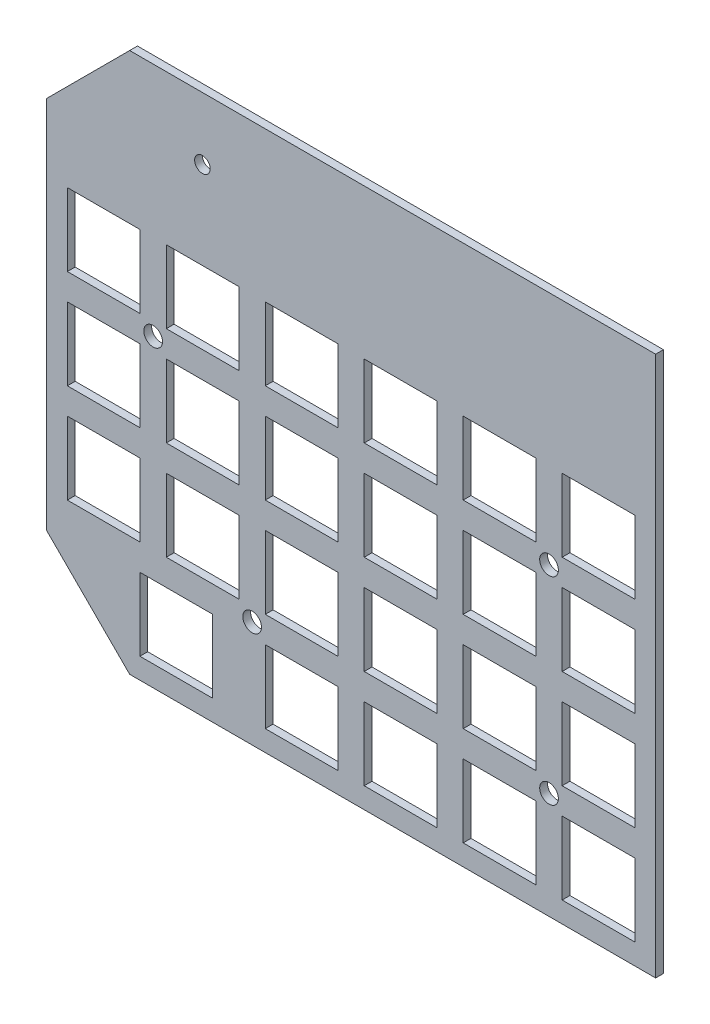
SolidWorks part; units mm, degrees
material "Alliage 1060"
ref_plane "Plan de face" through (0, 0, 0) normal (0, 0, 1) x (1, 0, 0)
ref_plane "Plan de dessus" through (0, 0, 0) normal (0, 1, 0) x (1, 0, 0)
ref_plane "Plan de droite" through (0, 0, 0) normal (1, 0, 0) x (0, 0, -1)
other "Centre de masse"
sketch "Esquisse1" plane through (0, 0, 0) normal (0, 0, 1) x (1, 0, 0)
  line L0 (0, -85) -> (16, -101)
  line L4 (117.25, 3) -> (117.25, -101)
  line L5 (16, 3) -> (0, -13)
  line L7 (117.25, 3) -> (16, 3)
  line L8 (0, -13) -> (0, -85)
  line L9 (16, -101) -> (117.25, -101)
  dimension "D1" = 104
  dimension "D2" = 117.25
  dimension "D3" = 16
  dimension "D4" = 16
  dimension "D5" = 16
  dimension "D6" = 16
extrude "Boss.-Extru.1" add sketch "Esquisse1" along normal blind 1.5
sketch "Esquisse2" plane through (0, 0, 1.5) normal (0, 0, 1) x (1, 0, 0)
  line L0 (0, -13) -> (0, -85) construction
  line L1 (4, -25.85) -> (18, -25.85)
  line L2 (4, -25.85) -> (4, -39.85)
  line L3 (4, -39.85) -> (18, -39.85)
  line L4 (18, -25.85) -> (18, -39.85)
  line L5 (11, -39.85) -> (11, -25.85) construction
  line L6 (4, -32.85) -> (18, -32.85) construction
  line L7 (117.25, 3) -> (16, 3) construction
  line L8 (117.25, -101) -> (117.25, 3) construction
  line L12 (23.05, -25.85) -> (23.05, -39.85)
  line L13 (23.05, -25.85) -> (37.05, -25.85)
  line L14 (37.05, -25.85) -> (37.05, -39.85)
  line L15 (23.05, -39.85) -> (37.05, -39.85)
  line L16 (42.1, -25.85) -> (42.1, -39.85)
  line L17 (42.1, -25.85) -> (56.1, -25.85)
  line L18 (56.1, -25.85) -> (56.1, -39.85)
  line L19 (42.1, -39.85) -> (56.1, -39.85)
  line L20 (61.15, -25.85) -> (61.15, -39.85)
  line L21 (61.15, -25.85) -> (75.15, -25.85)
  line L22 (75.15, -25.85) -> (75.15, -39.85)
  line L23 (61.15, -39.85) -> (75.15, -39.85)
  line L24 (80.2, -25.85) -> (80.2, -39.85)
  line L25 (80.2, -25.85) -> (94.2, -25.85)
  line L26 (94.2, -25.85) -> (94.2, -39.85)
  line L27 (80.2, -39.85) -> (94.2, -39.85)
  line L28 (99.25, -25.85) -> (99.25, -39.85)
  line L29 (99.25, -25.85) -> (113.25, -25.85)
  line L30 (113.25, -25.85) -> (113.25, -39.85)
  line L31 (99.25, -39.85) -> (113.25, -39.85)
  line L32 (23.05, -44.9) -> (23.05, -58.9)
  line L33 (23.05, -44.9) -> (37.05, -44.9)
  line L34 (37.05, -44.9) -> (37.05, -58.9)
  line L35 (23.05, -58.9) -> (37.05, -58.9)
  line L36 (42.1, -44.9) -> (42.1, -58.9)
  line L37 (42.1, -44.9) -> (56.1, -44.9)
  line L38 (56.1, -44.9) -> (56.1, -58.9)
  line L39 (42.1, -58.9) -> (56.1, -58.9)
  line L40 (61.15, -44.9) -> (61.15, -58.9)
  line L41 (61.15, -44.9) -> (75.15, -44.9)
  line L42 (75.15, -44.9) -> (75.15, -58.9)
  line L43 (61.15, -58.9) -> (75.15, -58.9)
  line L44 (80.2, -44.9) -> (80.2, -58.9)
  line L45 (80.2, -44.9) -> (94.2, -44.9)
  line L46 (94.2, -44.9) -> (94.2, -58.9)
  line L47 (80.2, -58.9) -> (94.2, -58.9)
  line L48 (99.25, -44.9) -> (99.25, -58.9)
  line L49 (99.25, -44.9) -> (113.25, -44.9)
  line L50 (113.25, -44.9) -> (113.25, -58.9)
  line L51 (99.25, -58.9) -> (113.25, -58.9)
  line L52 (23.05, -63.95) -> (23.05, -77.95)
  line L53 (23.05, -63.95) -> (37.05, -63.95)
  line L54 (37.05, -63.95) -> (37.05, -77.95)
  line L55 (23.05, -77.95) -> (37.05, -77.95)
  line L56 (42.1, -63.95) -> (42.1, -77.95)
  line L57 (42.1, -63.95) -> (56.1, -63.95)
  line L58 (56.1, -63.95) -> (56.1, -77.95)
  line L59 (42.1, -77.95) -> (56.1, -77.95)
  line L60 (61.15, -63.95) -> (61.15, -77.95)
  line L61 (61.15, -63.95) -> (75.15, -63.95)
  line L62 (75.15, -63.95) -> (75.15, -77.95)
  line L63 (61.15, -77.95) -> (75.15, -77.95)
  line L64 (80.2, -63.95) -> (80.2, -77.95)
  line L65 (80.2, -63.95) -> (94.2, -63.95)
  line L66 (94.2, -63.95) -> (94.2, -77.95)
  line L67 (80.2, -77.95) -> (94.2, -77.95)
  line L68 (99.25, -63.95) -> (99.25, -77.95)
  line L69 (99.25, -63.95) -> (113.25, -63.95)
  line L70 (113.25, -63.95) -> (113.25, -77.95)
  line L71 (99.25, -77.95) -> (113.25, -77.95)
  line L72 (4, -44.9) -> (4, -58.9)
  line L73 (4, -44.9) -> (18, -44.9)
  line L74 (18, -44.9) -> (18, -58.9)
  line L75 (4, -58.9) -> (18, -58.9)
  line L76 (4, -63.95) -> (4, -77.95)
  line L77 (4, -63.95) -> (18, -63.95)
  line L78 (18, -63.95) -> (18, -77.95)
  line L79 (4, -77.95) -> (18, -77.95)
  line L112 (42.1, -83) -> (42.1, -97)
  line L113 (42.1, -83) -> (56.1, -83)
  line L114 (56.1, -83) -> (56.1, -97)
  line L115 (42.1, -97) -> (56.1, -97)
  line L116 (61.15, -83) -> (61.15, -97)
  line L117 (61.15, -83) -> (75.15, -83)
  line L118 (75.15, -83) -> (75.15, -97)
  line L119 (61.15, -97) -> (75.15, -97)
  line L120 (80.2, -83) -> (80.2, -97)
  line L121 (80.2, -83) -> (94.2, -83)
  line L122 (94.2, -83) -> (94.2, -97)
  line L123 (80.2, -97) -> (94.2, -97)
  line L124 (99.25, -83) -> (99.25, -97)
  line L125 (99.25, -83) -> (113.25, -83)
  line L126 (113.25, -83) -> (113.25, -97)
  line L127 (99.25, -97) -> (113.25, -97)
  line L128 (4, -83) -> (4, -97) [skipped]
  line L129 (4, -83) -> (18, -83) [skipped]
  line L130 (18, -83) -> (18, -97) [skipped]
  line L131 (4, -97) -> (18, -97) [skipped]
  line L132 (23.05, -83) -> (23.05, -97) [skipped]
  line L133 (23.05, -83) -> (37.05, -83) [skipped]
  line L134 (37.05, -83) -> (37.05, -97) [skipped]
  line L135 (23.05, -97) -> (37.05, -97) [skipped]
  line L137 (17.97, -83) -> (31.97, -83)
  line L138 (17.97, -83) -> (17.97, -97)
  line L139 (17.97, -97) -> (31.97, -97)
  line L140 (31.97, -83) -> (31.97, -97)
  line L141 (24.97, -97) -> (24.97, -83) construction
  line L142 (17.97, -90) -> (31.97, -90) construction
  line L143 (16, -101) -> (117.25, -101) construction
  circle A8 centre (30, -9) radius 1.5
  point P0 (11, -32.85)
  point P19 (24.97, -90)
  dimension "D5" = 4
  dimension "D13" = 5.05
  dimension "D7" = 12
  dimension "D6" = 30
  dimension "D1" = 14
  dimension "D2" = 14
  dimension "D3" = 4
  dimension "D4" = 6
  dimension "D9" = 14
  dimension "D10" = 14
  dimension "D11" = 10.13
  dimension "D12" = 5.05
  dimension "D8" = 4
extrude "Enlèv. mat.-Extru.1" cut sketch "Esquisse2" against normal blind 1.5
sketch "Esquisse9" plane through (0, 0, 1.5) normal (0, 0, 1) x (1, 0, 0)
  line L0 (18, -44.9) -> (23.05, -39.85) construction
  line L1 (94.2, -39.85) -> (99.25, -44.9) construction
  line L2 (94.2, -83) -> (99.25, -77.95) construction
  line L3 (37.05, -77.95) -> (42.1, -83) construction
  point P16 (20.525, -42.375)
  point P17 (39.575, -80.475)
  point P18 (96.725, -42.375)
  point P19 (96.725, -80.475)
hole_wizard "Dégagement M31" positions "Esquisse17" profile "Esquisse18" hole size "M3" standard "Ansi Metric" end condition through all
sketch "Esquisse17" plane through (0, 0, 1.5) normal (0, 0, 1) x (1, 0, 0)
  point P0 (20.525, -42.375)
  point P4 (96.725, -42.375)
  point P7 (96.725, -80.475)
  point P10 (39.575, -80.475)
sketch "Esquisse18" plane through (20.525, -42.375, 1.5) normal (1, 0, 0) x (0, -1, 0)
  line L0 (0, 0) -> (0, 1.5)
  line L1 (0, 1.5) -> (1.8, 1.5)
  line L2 (1.8, 1.5) -> (1.8, 0)
  line L5 (1.8, 0) -> (0, 0)
  line L11 (0, -6.35) -> (0, 107.95) construction
  dimension "Diamètre du perçage jusqu'au prochain" = 3.6
  dimension "Profondeur du perçage jusqu'au prochain" = 1.5
